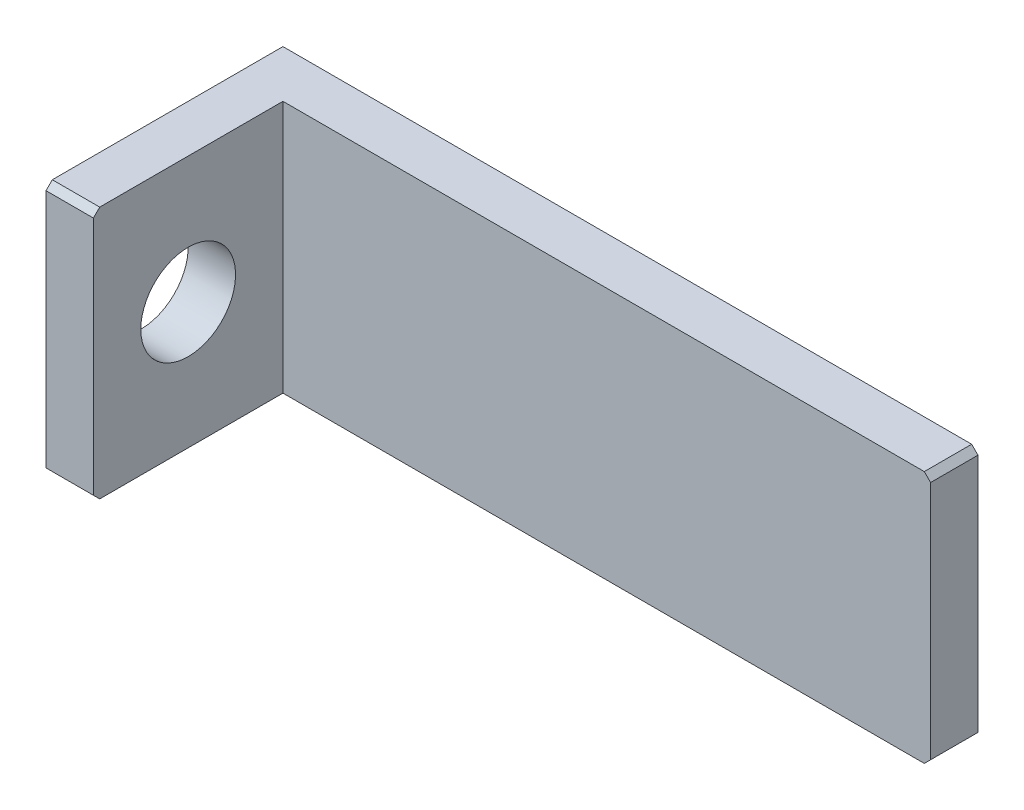
SolidWorks part; units mm, degrees
ref_plane "Front Plane" through (0, 0, 0) normal (0, 0, 1) x (1, 0, 0)
ref_plane "Top Plane" through (0, 0, 0) normal (0, 1, 0) x (1, 0, 0)
ref_plane "Right Plane" through (0, 0, 0) normal (1, 0, 0) x (0, 0, -1)
ref_plane "Plane1" through (0, 0, -366.3577) normal (0, 0, 1) x (1, 0, 0)
sketch "Sketch1" plane through (0, 0, -366.3577) normal (0, 0, 1) x (1, 0, 0)
  line L0 (-160.5071, 663.332) -> (-138.5071, 663.332)
  line L1 (-138.5071, 663.332) -> (-138.5071, 671.332)
  line L2 (-138.5071, 671.332) -> (-160.5071, 671.332)
  line L3 (-160.5071, 671.332) -> (-160.5071, 663.332)
extrude "Boss-Extrude1" add sketch "Sketch1" against normal blind 7.5
sketch "Sketch2" plane through (0, 663.332, 0) normal (0, -1, 0) x (1, 0, 0)
  line L0 (-138.5071, -366.3577) -> (-159.0071, -366.3577)
  line L1 (-159.0071, -366.3577) -> (-159.0071, -372.3577)
  line L2 (-159.0071, -372.3577) -> (-138.5071, -372.3577)
  line L3 (-138.5071, -372.3577) -> (-138.5071, -366.3577)
extrude "Cut-Extrude1" cut sketch "Sketch2" against normal through all
hole_wizard "Ø3.0 (3) Diameter Hole1" positions "Sketch4" profile "Sketch3" hole size "Ø3.0" standard "ANSI Metric"
sketch "Sketch4" plane through (-160.5071, 0, 0) normal (-1, 0, 0) x (0, 0, 1)
  point P0 (-369.3577, 667.332)
sketch "Sketch3" plane through (-160.5071, 667.332, -369.3577) normal (0, 1, 0) x (0, 0, 1)
  line L0 (0, 0) -> (0, 22)
  line L1 (0, 22) -> (1.5, 22)
  line L2 (1.5, 22) -> (1.5, 0)
  line L5 (1.5, 0) -> (0, 0)
  line L11 (0, -6.35) -> (0, 107.95) construction
  dimension "Thru Hole Dia." = 3
  dimension "Thru Hole Depth" = 22
chamfer "Chamfer1" distance 0.2 angle 45 4 edges at (-138.5071, 663.332, -373.1077) (-138.5071, 671.332, -373.1077) (-159.7571, 671.332, -366.3577) (-159.7571, 663.332, -366.3577)
